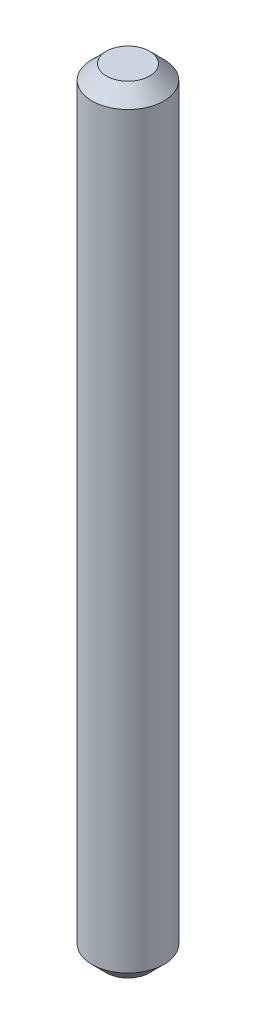
SolidWorks part; units mm, degrees
ref_plane "Front Plane" through (0, 0, 0) normal (0, 0, 1) x (1, 0, 0)
ref_plane "Top Plane" through (0, 0, 0) normal (0, 1, 0) x (1, 0, 0)
ref_plane "Right Plane" through (0, 0, 0) normal (1, 0, 0) x (0, 0, -1)
sketch "Sketch3" plane through (0, 0, 0) normal (0, 1, 0) x (1, 0, 0)
  circle A0 centre (0, 0) radius 2.5
  dimension "D1" = 5
extrude "Boss-Extrude1" add sketch "Sketch3" along normal blind 54
chamfer "Chamfer2" distance 1 angle 45 2 edges at (0, 0, 2.5) (0, 54, 2.5)
